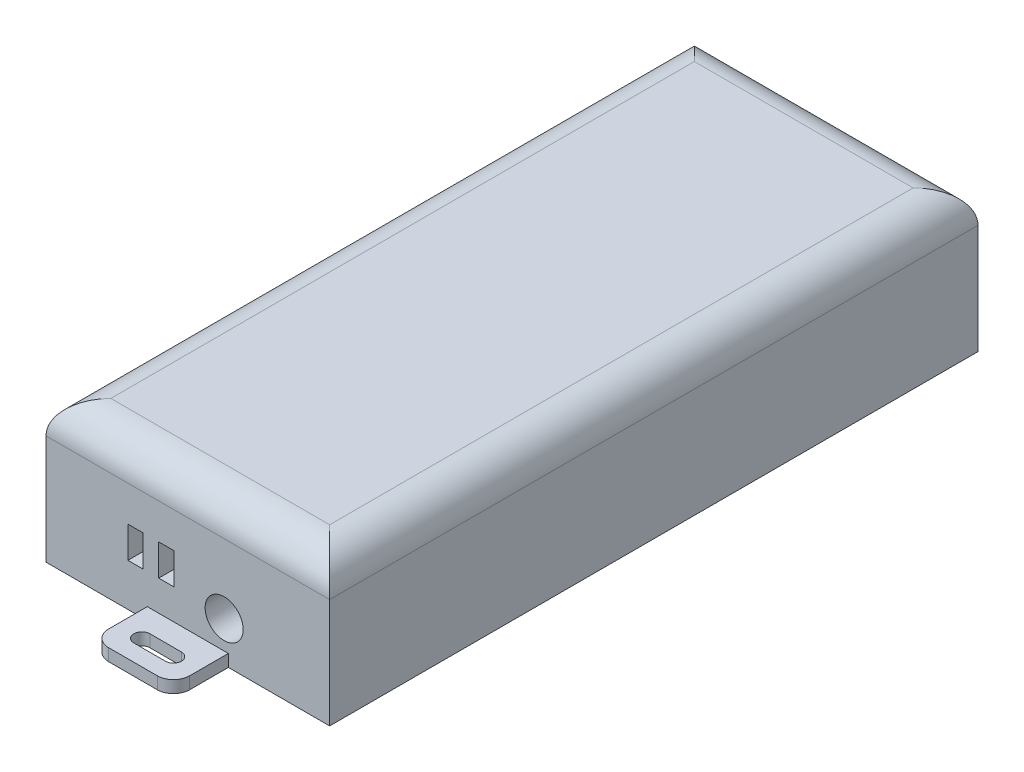
SolidWorks part; units mm, degrees
ref_plane "Front Plane" through (0, 0, 0) normal (0, 0, 1) x (1, 0, 0)
ref_plane "Top Plane" through (0, 0, 0) normal (0, 1, 0) x (1, 0, 0)
ref_plane "Right Plane" through (0, 0, 0) normal (1, 0, 0) x (0, 0, -1)
sketch "Sketch1" plane through (0, 0, 0) normal (0, 1, 0) x (1, 0, 0)
  line L1 (0, 0) -> (44.45, 0)
  line L2 (0, 0) -> (0, 101.6)
  line L3 (0, 101.6) -> (44.45, 101.6)
  line L4 (44.45, 0) -> (44.45, 101.6)
  dimension "D1" = 44.45
  dimension "D2" = 101.6
extrude "Boss-Extrude1" add sketch "Sketch1" along normal blind 22.225
fillet "Fillet1" radius 5.08 4 edges at (22.225, 22.225, -101.6) (44.45, 22.225, -50.8) (22.225, 22.225, 0) (0, 22.225, -50.8)
sketch "Sketch2" plane through (0, 0, 0) normal (0, 0, 1) x (1, 0, 0)
  circle A0 centre (27.9151, 6.2942) radius 2.9815
  point P2 (27.9151, 6.2942)
extrude "Cut-Extrude1" cut sketch "Sketch2" against normal blind 12.7
sketch "Sketch3" plane through (0, 0, 0) normal (0, 0, 1) x (1, 0, 0)
  line L1 (12.838, 11.5871) -> (15.2257, 11.5871)
  line L2 (12.838, 11.5871) -> (12.838, 6.6724)
  line L3 (12.838, 6.6724) -> (15.2257, 6.6724)
  line L4 (15.2257, 11.5871) -> (15.2257, 6.6724)
  line L5 (17.6657, 11.5871) -> (20.0535, 11.5871)
  line L6 (17.6657, 11.5871) -> (17.6657, 6.6724)
  line L7 (17.6657, 6.6724) -> (20.0535, 6.6724)
  line L8 (20.0535, 11.5871) -> (20.0535, 6.6724)
extrude "Cut-Extrude2" cut sketch "Sketch3" against normal blind 7.62
sketch "Sketch4" plane through (0, 0, -101.6) normal (0, 0, -1) x (-1, 0, 0)
  line L0 (-27.4959, 9.5518) -> (-26.2003, 9.5518) construction
  line L1 (-30.8234, 9.5518) -> (-27.4959, 9.5518)
  line L2 (-30.8234, 9.5518) -> (-30.8234, 4.1926)
  line L3 (-30.8234, 4.1926) -> (-27.4959, 4.1926)
  line L4 (-27.4959, 9.5518) -> (-27.4959, 4.1926)
  line L5 (-26.2003, 9.5518) -> (-22.8728, 9.5518)
  line L6 (-26.2003, 9.5518) -> (-26.2003, 4.1926)
  line L7 (-26.2003, 4.1926) -> (-22.8728, 4.1926)
  line L8 (-22.8728, 9.5518) -> (-22.8728, 4.1926)
  line L9 (-21.5772, 9.5518) -> (-18.2497, 9.5518)
  line L10 (-21.5772, 9.5518) -> (-21.5772, 4.1926)
  line L11 (-21.5772, 4.1926) -> (-18.2497, 4.1926)
  line L12 (-18.2497, 9.5518) -> (-18.2497, 4.1926)
  line L13 (-16.9541, 9.5518) -> (-13.6266, 9.5518)
  line L14 (-16.9541, 9.5518) -> (-16.9541, 4.1926)
  line L15 (-16.9541, 4.1926) -> (-13.6266, 4.1926)
  line L16 (-13.6266, 9.5518) -> (-13.6266, 4.1926)
  line L17 (-22.8728, 9.5518) -> (-21.5772, 9.5518) construction
  line L18 (-18.2497, 9.5518) -> (-16.9541, 9.5518) construction
  line L19 (-44.45, 0) -> (0, 0) construction
  point P16 (-30.6761, 4.6637)
  point P17 (-29.2627, 4.7226)
  point P18 (-19.0153, 10.2586)
  point P19 (-18.6031, 9.5518)
  point P20 (-15.1284, 9.6107)
  point P21 (-14.5395, 4.3692)
  point P22 (-20.8999, 4.2515)
  point P25 (-22.225, 0)
  point P26 (-22.225, 9.5518)
extrude "Cut-Extrude3" cut sketch "Sketch4" against normal blind 7.62
sketch "Sketch5" plane through (0, 0, 0) normal (0, -1, 0) x (1, 0, 0)
  line L0 (15.875, 0) -> (15.875, 6.0583)
  line L1 (0, 0) -> (44.45, 0) construction
  line L2 (18.415, 8.5983) -> (26.035, 8.5983)
  line L3 (28.575, 6.0583) -> (28.575, 0)
  line L4 (15.875, 0) -> (28.575, 0)
  line L7 (19.7514, 5.9847) -> (24.6986, 5.9847)
  line L8 (24.6986, 3.4764) -> (19.7514, 3.4764)
  arc A0 (26.035, 8.5983) -> (28.575, 6.0583) centre (26.035, 6.0583) cw
  arc A1 (18.415, 8.5983) -> (15.875, 6.0583) centre (18.415, 6.0583) ccw
  arc A4 (24.6986, 5.9847) -> (24.6986, 3.4764) centre (24.6986, 4.7305) cw
  arc A5 (19.7514, 3.4764) -> (19.7514, 5.9847) centre (19.7514, 4.7305) cw
  point P7 (22.225, 8.5983)
  point P8 (22.225, 0)
  point P18 (22.225, 5.9847)
  point P19 (24.6986, 5.2623)
  dimension "D1" = 2.54
  dimension "D3" = 12.7
extrude "Boss-Extrude2" add sketch "Sketch5" against normal blind 1.905
ref_point "Point1"
ref_plane "Plane3" through (0, 0, -49.7381) normal (0, 0, 1) x (1, 0, 0)
mirror "Mirror2" about plane through (0, 0, -49.7381) normal (0, 0, 1) of "Boss-Extrude2"
